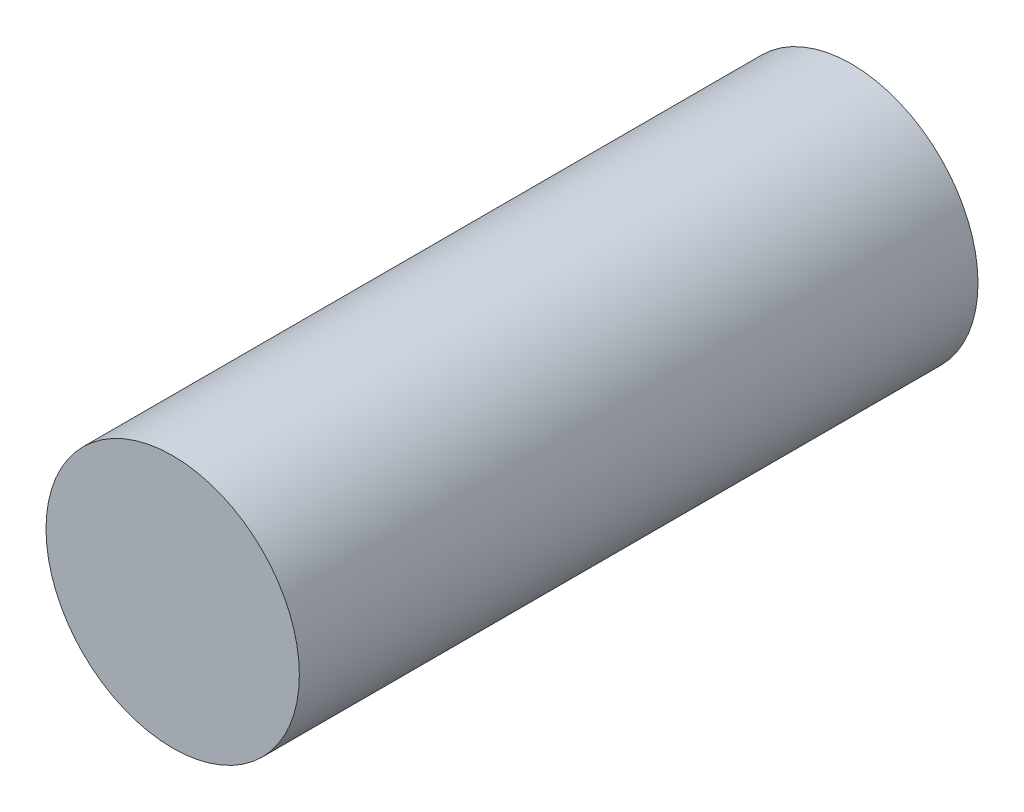
SolidWorks part; units mm, degrees
ref_plane "Front" through (0, 0, 0) normal (0, 0, 1) x (1, 0, 0)
ref_plane "Top" through (0, 0, 0) normal (0, 1, 0) x (1, 0, 0)
ref_plane "Right" through (0, 0, 0) normal (1, 0, 0) x (0, 0, -1)
sketch "Sketch1" plane through (0, 0, 0) normal (0, 0, 1) x (1, 0, 0)
  line L0 (0, 0) -> (0, 30) construction
  line L1 (0, 0) -> (28.5317, 9.2705) construction
  line L2 (0, 0) -> (-28.3656, 9.767) construction
  line L3 (0, 0) -> (28.6891, 8.7712) construction
  line L4 (0, 0) -> (0.5236, 29.9954) construction
  line L5 (0, 0) -> (-28.5317, 9.2705) construction
  line L6 (0, 0) -> (-18.0545, -23.9591) construction
  line L7 (0, 0) -> (-17.6336, -24.2705) construction
  line L8 (0, 0) -> (17.2073, -24.5746) construction
  line L9 (0, 0) -> (17.6336, -24.2705) construction
  line L10 (0, 0) -> (-2.6147, 29.8858) construction
  circle A0 centre (0, 0) radius 4.6
  circle A1 centre (0, 0) radius 5.6
  circle A2 centre (0, 0) radius 30
  circle A3 centre (0, 0) radius 27.5
  dimension "D1" = 9.2
  dimension "D2" = 11.2
  dimension "D3" = 55
  dimension "D4" = 60
extrude "Boss-Extrude6" add sketch "Sketch1" along normal blind 30 contours A1
sketch "Sketch5" plane through (0, 0, 30) normal (0, 0, 1) x (1, 0, 0)
  line L0 (0, 5.6) -> (13.1863, 24.1324) construction
  line L1 (0, 0) -> (0, 30) construction
  line L2 (0, 0) -> (15.9431, 22.4068) construction
  line L3 (13.1863, 24.1324) -> (0, 5.6)
  line L4 (5.3259, 1.7305) -> (18.5437, 20.3071) construction
  line L5 (18.5437, 20.3071) -> (5.3259, 1.7305)
  line L6 (0, 0) -> (28.5317, 9.2705) construction
  line L7 (0, 0) -> (0.5236, 29.9954) construction
  circle A0 centre (0, 0) radius 4.6
  arc A5 (18.5437, 20.3071) -> (13.2087, 24.1201) centre (0, 0) ccw
  arc A6 (5.3259, 1.7305) -> (0.0977, 5.5991) centre (0, 0) ccw
  circle A13 centre (0, 0) radius 5.6 construction
  circle A14 centre (0, 0) radius 27.5 construction
